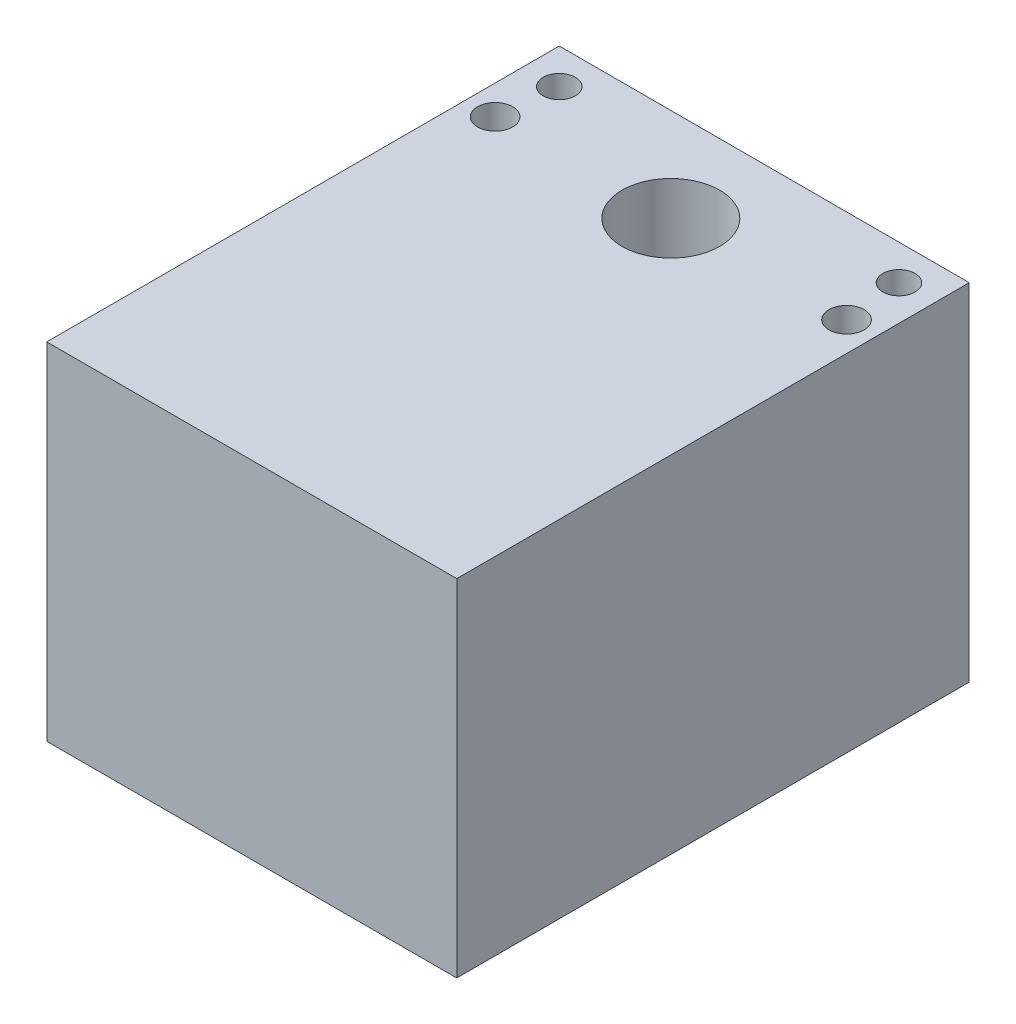
SolidWorks part; units mm, degrees
ref_plane "前视基准面" through (0, 0, 0) normal (0, 0, 1) x (1, 0, 0)
ref_plane "上视基准面" through (0, 0, 0) normal (0, 1, 0) x (1, 0, 0)
ref_plane "右视基准面" through (0, 0, 0) normal (1, 0, 0) x (0, 0, -1)
sketch "草图1" plane through (0, 0, 0) normal (0, 1, 0) x (1, 0, 0)
  line L0 (0, 22.225) -> (0, -22.225) construction
  line L5 (-17.78, 22.225) -> (17.78, 22.225)
  line L6 (-17.78, 22.225) -> (-17.78, -22.225)
  line L7 (-17.78, -22.225) -> (17.78, -22.225)
  line L8 (17.78, 22.225) -> (17.78, -22.225)
  line L9 (-17.78, 22.225) -> (17.78, -22.225) construction
  line L10 (-17.78, -22.225) -> (17.78, 22.225) construction
  line L11 (-14.732, 19.177) -> (-17.78, 22.225) construction
  line L12 (-15.24, 14.122) -> (15.24, 14.122) construction
  circle A0 centre (-14.732, 19.177) radius 1.397
  circle A1 centre (14.732, 19.177) radius 1.397
  circle A2 centre (-15.24, 14.122) radius 1.524
  circle A3 centre (15.24, 14.122) radius 1.524
  circle A4 centre (0, 14.122) radius 4.2333
  point P0 (0, 0)
  dimension "D3" = 2.794
  dimension "D4" = 2.794
  dimension "D8" = 3.048
  dimension "D9" = 3.048
  dimension "D12" = 8.4667
  dimension "D1" = 35.56
  dimension "D2" = 44.45
  dimension "D5" = 29.464
  dimension "D6" = 3.048
  dimension "D7" = 3.048
  dimension "D10" = 30.48
  dimension "D11" = 8.103
extrude "凸台-拉伸1" add sketch "草图1" along normal blind 30
